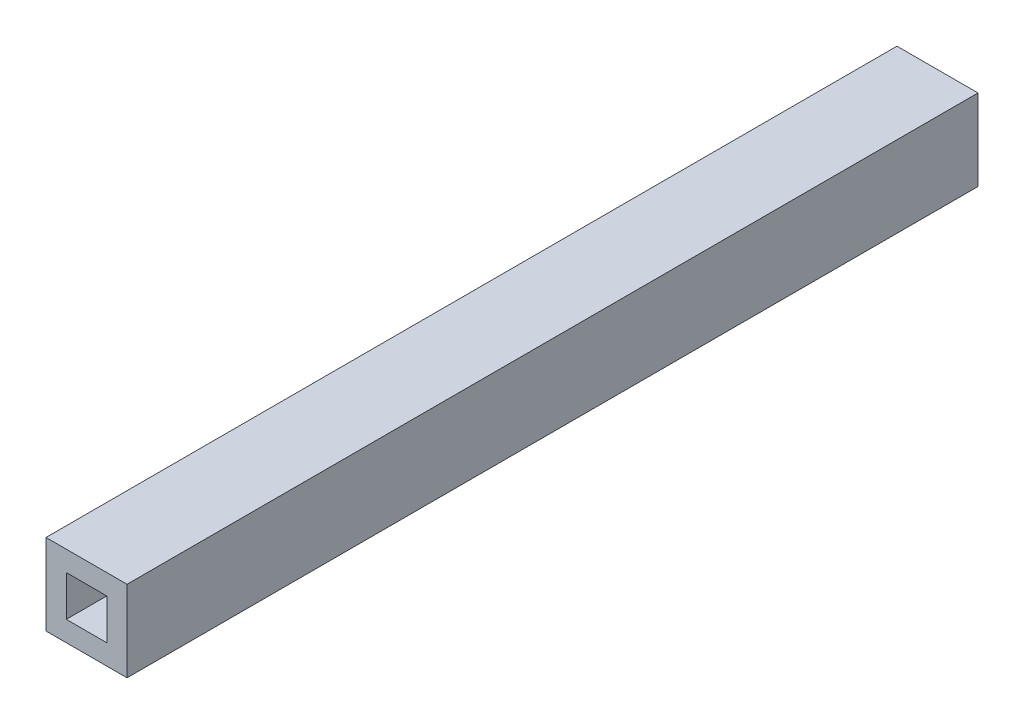
SolidWorks part; units mm, degrees
material "6063-O"
ref_plane "Front Plane" through (0, 0, 0) normal (0, 0, 1) x (1, 0, 0)
ref_plane "Top Plane" through (0, 0, 0) normal (0, 1, 0) x (1, 0, 0)
ref_plane "Right Plane" through (0, 0, 0) normal (1, 0, 0) x (0, 0, -1)
sketch "Sketch1" plane through (0, 0, 0) normal (0, 0, 1) x (1, 0, 0)
  line L1 (-10, -10) -> (10, -10)
  line L2 (-10, -10) -> (-10, 10)
  line L3 (-10, 10) -> (10, 10)
  line L4 (10, -10) -> (10, 10)
  line L5 (-10, -10) -> (10, 10) construction
  line L6 (-10, 10) -> (10, -10) construction
  point P0 (0, 0)
  dimension "D1" = 20
extrude "Extrude-Thin1" add sketch "Sketch1" along normal blind 210 thin thin type one direction reverse wall 5
